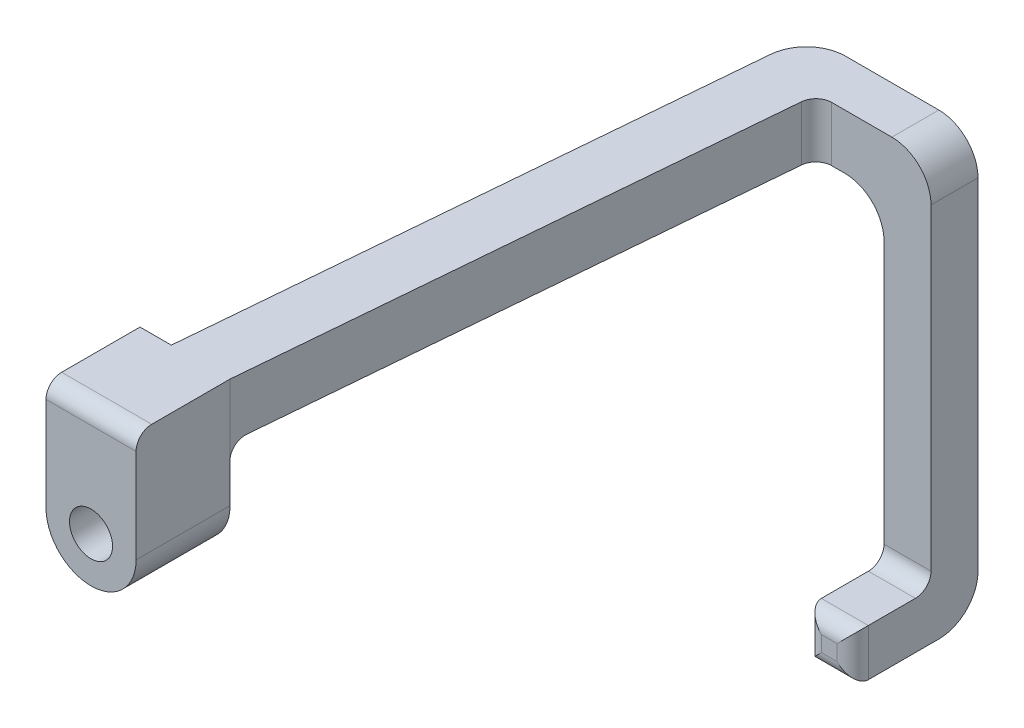
SolidWorks part; units mm, degrees
ref_plane "Front Plane" through (0, 0, 0) normal (1, 0, 0) x (0, 1, 0)
ref_plane "Top Plane" through (0, 0, 0) normal (0, 0, 1) x (0, 1, 0)
ref_plane "Right Plane" through (0, 0, 0) normal (0, 1, 0) x (-1, 0, 0)
sketch "Sketch1" plane through (0, 0, 0) normal (0, 0, 1) x (0, 1, 0)
  line L0 (0, 0) -> (1.375, 0) construction
  line L3 (0, 2.875) -> (7, 2.875)
  line L4 (0, -2.875) -> (7, -2.875)
  line L5 (7, -2.875) -> (7, 2.875)
  arc A0 (0, 2.875) -> (0, -2.875) centre (0, 0) ccw
  circle A3 centre (0, 0) radius 1.375
  point P2 (0, 0)
  dimension "D1" = 2.75
  dimension "D2" = 2.875
  dimension "D3" = 7
extrude "Boss-Extrude1" add sketch "Sketch1" along normal blind 6
sketch "Sketch2" plane through (0, 0, 0) normal (0, 0, -1) x (1, 0, 0)
  line L0 (2.875, -7) -> (-2.875, -7) construction
  line L1 (2.875, -7) -> (-0.875, -7)
  line L4 (2.875, -3.5) -> (2.875, -7)
  line L5 (-0.875, -7) -> (-0.875, -3.5)
  line L6 (-0.875, -3.5) -> (2.875, -3.5)
  line L7 (2.875, 0) -> (2.875, -7) construction
  line L8 (-2.875, -7) -> (-2.875, 0) construction
  dimension "D1" = 2
ref_plane "Plane1" through (0, 0, -37.5) normal (0, 0, -1) x (-1, 0, 0)
sketch "Sketch8" plane through (0, 0, -37.5) normal (0, 0, -1) x (-1, 0, 0)
  line L0 (-2.875, 3.5) -> (-2.875, 7) construction
  line L1 (0.875, 3.5) -> (-2.875, 3.5) construction
  line L2 (0.875, 7) -> (0.875, 3.5) construction
  line L3 (-2.875, 7) -> (0.875, 7) construction
  line L4 (-2.875, 3.5) -> (-2.875, 7) construction
  line L5 (0.875, 3.5) -> (-2.875, 3.5) construction
  line L6 (0.875, 7) -> (0.875, 3.5) construction
  line L7 (-2.875, 7) -> (0.875, 7) construction
  line L8 (-6.125, 3.5) -> (-6.125, 7)
  line L9 (-2.375, 3.5) -> (-2.375, 7)
  line L10 (-6.125, 7) -> (-2.375, 7)
  line L11 (-2.375, 3.5) -> (-6.125, 3.5)
  dimension "D1" = 3.25
loft "Loft1" add profiles "Sketch2", "Sketch8"
sketch "Sketch9" plane through (0, 0, 0) normal (1, 0, 0) x (0, 1, 0)
  line L0 (3.5, 0) -> (3.5, -37.5) construction
  line L1 (7, 0) -> (7, -37.5) construction
  line L2 (3.5, -34.5) -> (3.5, -37.5)
  line L3 (7, -34.5) -> (7, -37.5)
  line L4 (7, -37.5) -> (3.5, -37.5)
  line L6 (7, -34.5) -> (3.5, -34.5)
  dimension "D1" = 3
extrude "Boss-Extrude2" add sketch "Sketch9" along normal blind 7 and the other way up to surface from vertex
sketch "Sketch10" plane through (0, 7, 0) normal (0, 1, 0) x (-1, 0, 0)
  line L7 (-13.125, -37.5) -> (-6.125, -37.5) construction
  line L8 (-5.865, -34.5) -> (-13.125, -34.5) construction
  line L9 (-13.125, -37.5) -> (-13.125, -34.5) construction
  line L10 (-13.125, -37.5) -> (-10.125, -37.5)
  line L11 (-10.125, -34.5) -> (-13.125, -34.5)
  line L12 (-13.125, -37.5) -> (-13.125, -34.5)
  line L13 (-10.125, -34.5) -> (-10.125, -37.5)
  dimension "D1" = 3
extrude "Boss-Extrude3" add sketch "Sketch10" against normal blind 23.25 from surface
sketch "Sketch11" plane through (0, 0, -34.5) normal (0, 0, 1) x (1, 0, 0)
  line L1 (10.125, -19.75) -> (10.125, 3.5) construction
  line L8 (10.125, -19.75) -> (13.125, -19.75) construction
  line L9 (13.125, 7) -> (13.125, -19.75) construction
  line L10 (10.125, -19.75) -> (10.125, -16.75)
  line L11 (10.125, -19.75) -> (13.125, -19.75)
  line L12 (13.125, -16.75) -> (13.125, -19.75)
  line L13 (13.125, -16.75) -> (10.125, -16.75)
  dimension "D1" = 3
extrude "Boss-Extrude4" add sketch "Sketch11" along normal blind 5
fillet "Fillet1" radius 2.5 7 edges at (13.125, 7, -36) (11.625, -19.75, -37.5) (10.125, 3.5, -36)
fillet "Fillet2" radius 1 11 edges at (0, 7, 6) (5.865, 5.25, -34.5) (11.625, -16.75, -34.5) (11.625, -19.75, -29.5) (13.125, -18.25, -29.5) (11.625, -16.75, -29.5) (10.125, -18.25, -29.5)
